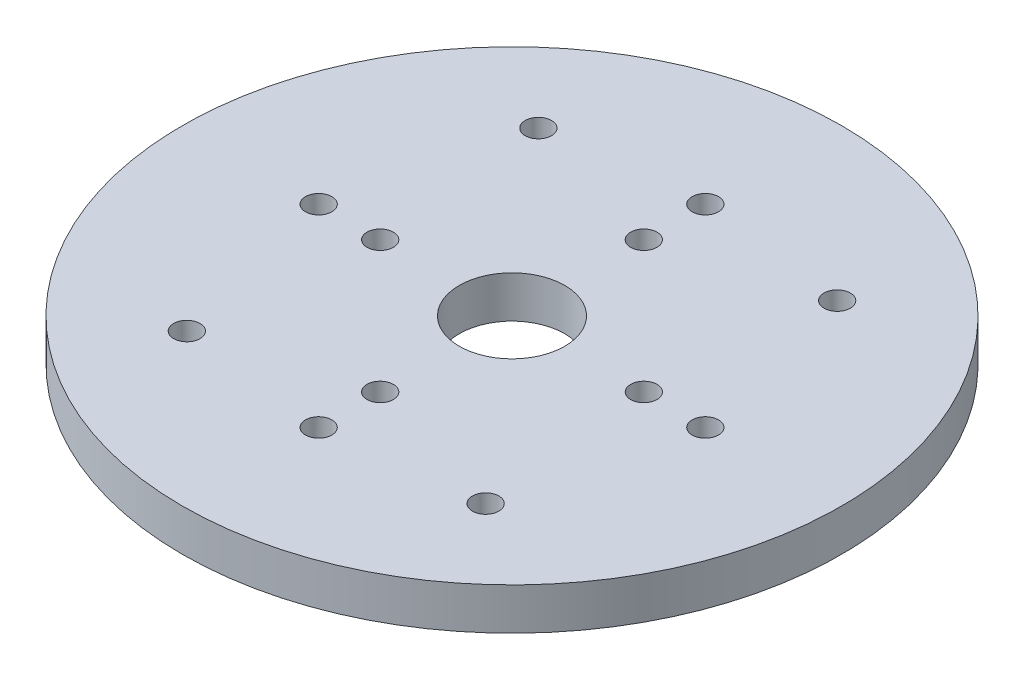
SolidWorks part; units mm, degrees
ref_plane "Front Plane" through (0, 0, 0) normal (0, 0, 1) x (1, 0, 0)
ref_plane "Top Plane" through (0, 0, 0) normal (0, 1, 0) x (1, 0, 0)
ref_plane "Right Plane" through (0, 0, 0) normal (1, 0, 0) x (0, 0, -1)
sketch "Sketch1" plane through (0, 0, 0) normal (0, 1, 0) x (1, 0, 0)
  circle A0 centre (0, 0) radius 37.5
  circle A1 centre (0, 0) radius 6
  circle A2 centre (0, 0) radius 25 construction
  circle A3 centre (0, 0) radius 30 construction
  circle A4 centre (0, 0) radius 44 construction
  dimension "D1" = 12
  dimension "D2" = 75
extrude "Boss-Extrude1" add sketch "Sketch1" along normal blind 4.7625
hole_wizard "Ø3.0mm Dowel Hole1" positions "Sketch5" profile "Sketch4" hole size "Ø3.0" standard "ANSI Metric" end condition through all
sketch "Sketch5" plane through (0, 0, 0) normal (0, -1, 0) x (-1, 0, 0)
  circle A0 centre (0, 0) radius 12.5
  circle A1 centre (0, 0) radius 15
  circle A2 centre (0, 0) radius 22
  point P40 (0, 15)
  point P42 (0, 22)
  point P44 (22, 0)
  point P46 (15, 0)
  point P48 (0, -15)
  point P50 (0, -22)
  point P52 (-15, 0)
  point P54 (-22, 0)
  dimension "D1" = 25
  dimension "D2" = 30
  dimension "D3" = 44
sketch "Sketch4" plane through (0, 0, -15) normal (1, 0, 0) x (0, 0, -1)
  line L0 (0, 0) -> (0, 4.7625)
  line L1 (0, 4.7625) -> (1.5, 4.7625)
  line L2 (1.5, 4.7625) -> (1.5, 0)
  line L5 (1.5, 0) -> (0, 0)
  line L11 (0, -6.35) -> (0, 107.95) construction
  dimension "Thru Hole Dia." = 3
  dimension "Thru Hole Depth" = 4.7625
hole_wizard "Ø3.0mm Dowel Hole4" positions "Sketch9" profile "Sketch8" hole size "Ø3.0" standard "ANSI Metric"
sketch "Sketch9" plane through (0, 4.7625, 0) normal (0, 1, 0) x (1, 0, 0)
  line L1 (-17, 20) -> (17, 20)
  line L2 (-17, 20) -> (-17, -20)
  line L3 (-17, -20) -> (17, -20)
  line L4 (17, 20) -> (17, -20)
  point P0 (-17, 20)
  point P1 (17, -20)
  point P82 (-17, -20)
  point P83 (17, 20)
  dimension "D1" = 40
  dimension "D2" = 20
  dimension "D3" = 34
  dimension "D4" = 17
sketch "Sketch8" plane through (-17, 4.7625, -20) normal (1, 0, 0) x (0, 0, 1)
  line L0 (0, 0) -> (0, 10.9013)
  line L1 (0, 10.9013) -> (1.5, 10)
  line L2 (1.5, 10) -> (1.5, 0)
  line L5 (1.5, 0) -> (0, 0)
  line L10 (0, 10.9013) -> (-1.5, 10) construction
  line L11 (0, -6.35) -> (0, 107.95) construction
  dimension "Hole Dia." = 3
  dimension "Hole Depth" = 10
  dimension "Drill Angle" = 118
